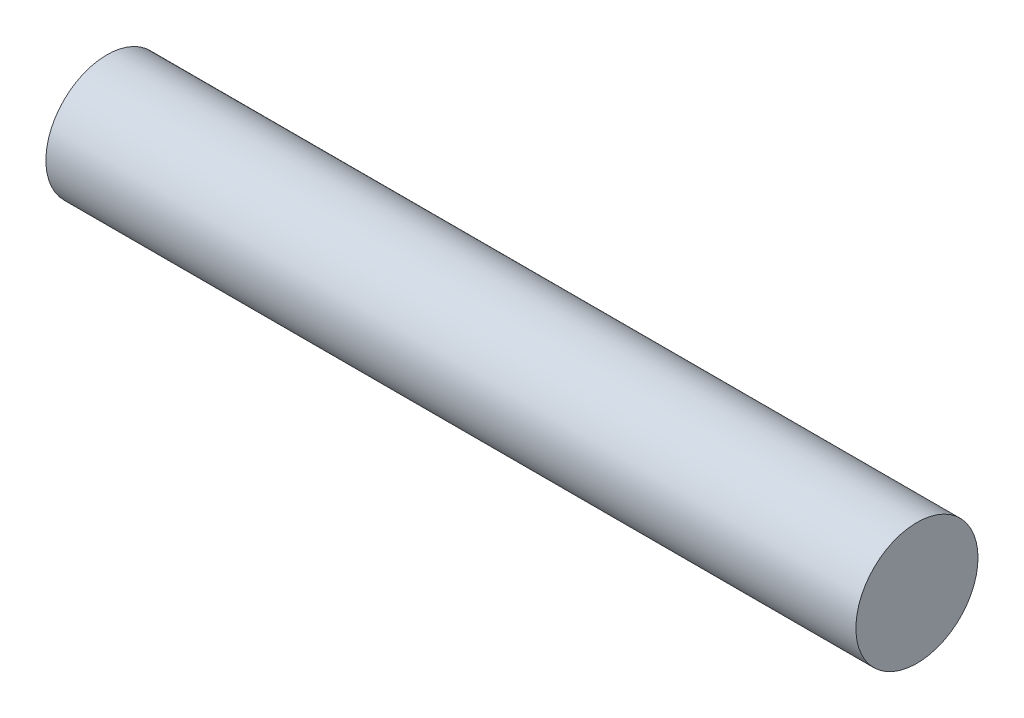
SolidWorks part; units mm, degrees
ref_plane "Front Plane" through (0, 0, 0) normal (0, 0, 1) x (1, 0, 0)
ref_plane "Top Plane" through (0, 0, 0) normal (0, 1, 0) x (1, 0, 0)
ref_plane "Right Plane" through (0, 0, 0) normal (1, 0, 0) x (0, 0, -1)
sketch "Croquis1" plane through (0, 0, 0) normal (0, 0, 1) x (1, 0, 0)
  line L0 (10.9466, 0) -> (-10.9466, 0) construction
  line L1 (-9.7376, 0) -> (-9.7376, 1.5)
  line L2 (-9.7376, 1.5) -> (10.1624, 1.5)
  line L3 (10.1624, 1.5) -> (10.1624, 0)
  line L4 (-9.7376, 0) -> (10.1624, 0)
  point P4 (0, 0)
  dimension "D1" = 19.9
  dimension "D2" = 3
revolve "Revolución1" add sketch "Croquis1" angle 360 about L0
